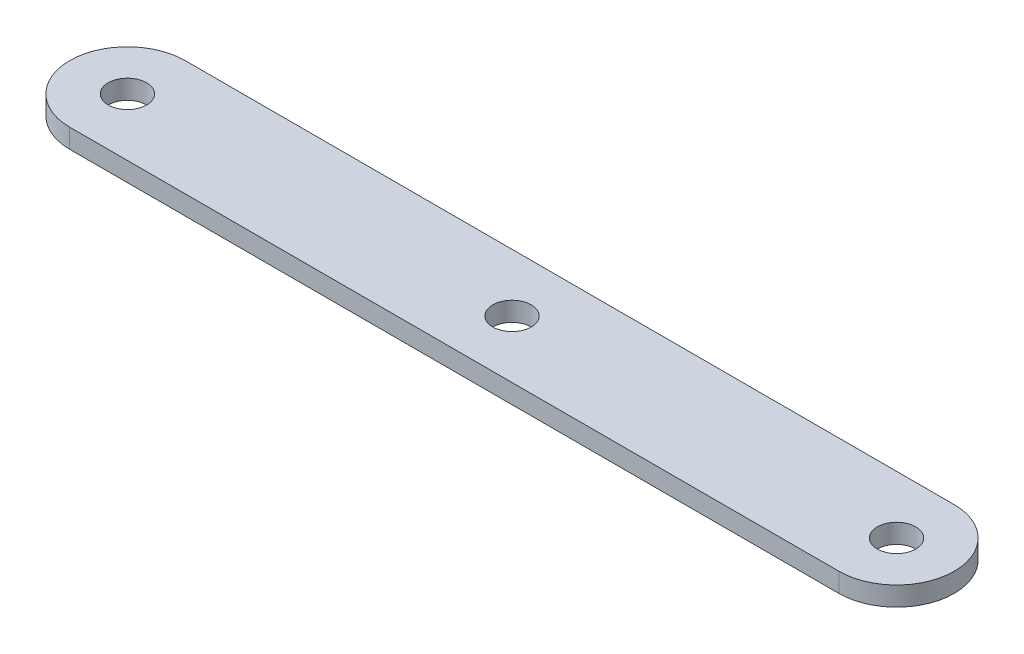
SolidWorks part; units mm, degrees
ref_plane "前视基准面" through (0, 0, 0) normal (0, 0, 1) x (1, 0, 0)
ref_plane "上视基准面" through (0, 0, 0) normal (0, 1, 0) x (1, 0, 0)
ref_plane "右视基准面" through (0, 0, 0) normal (1, 0, 0) x (0, 0, -1)
other "Configuration Table"
sketch "草图1" plane through (0, 0, 0) normal (0, 1, 0) x (1, 0, 0)
  line L0 (0, 0) -> (200, 0) construction
  line L1 (0, 15) -> (200, 15)
  line L2 (0, -15) -> (200, -15)
  arc A0 (0, 15) -> (0, -15) centre (0, 0) ccw
  arc A1 (200, -15) -> (200, 15) centre (200, 0) ccw
  circle A2 centre (200, 0) radius 5
  circle A3 centre (100, 0) radius 5
  circle A4 centre (0, 0) radius 5
  point P3 (100, 0)
  dimension "D2" = 15
  dimension "D3" = 10
  dimension "D4" = 10
  dimension "D5" = 10
  dimension "D1" = 200
extrude "凸台-拉伸1" add sketch "草图1" along normal blind 5
